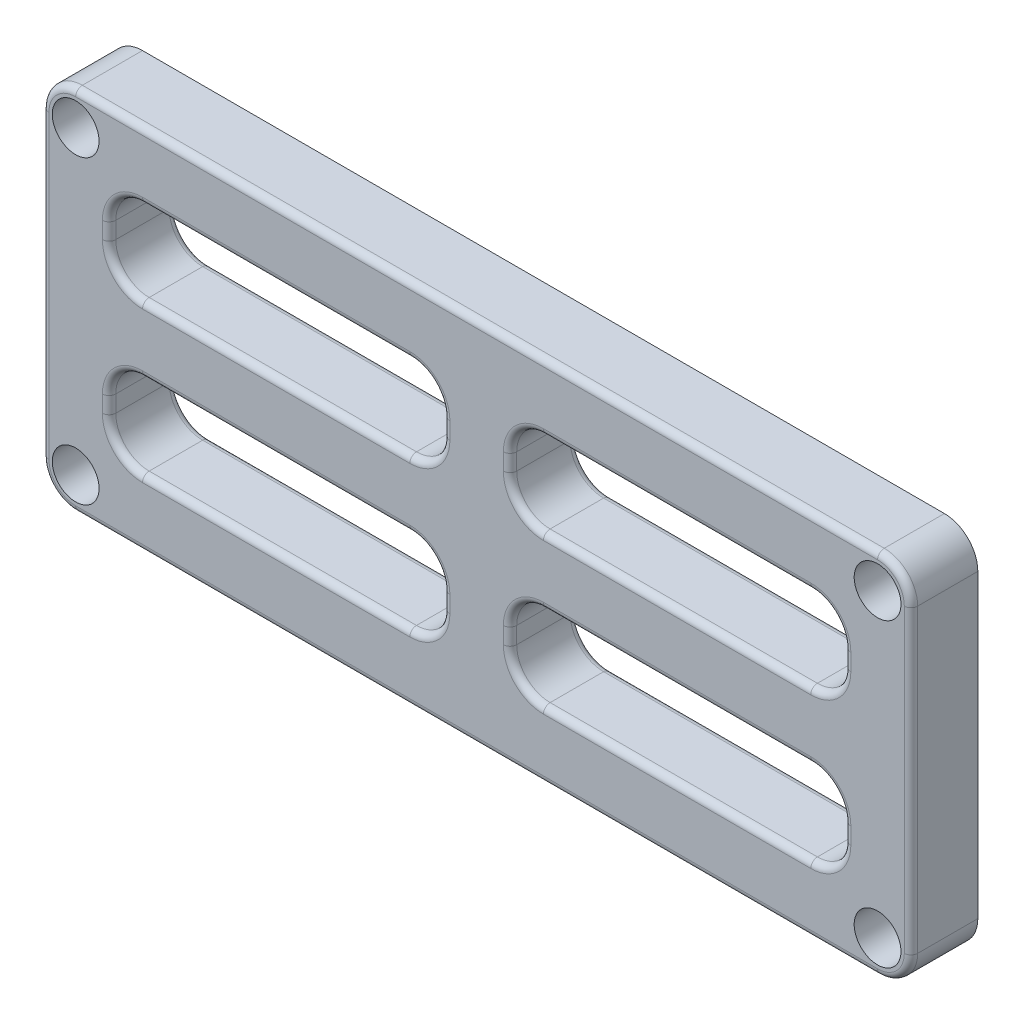
SolidWorks part; units mm, degrees
ref_plane "Front Plane" through (0, 0, 0) normal (0, 0, 1) x (1, 0, 0)
ref_plane "Top Plane" through (0, 0, 0) normal (0, 1, 0) x (1, 0, 0)
ref_plane "Right Plane" through (0, 0, 0) normal (1, 0, 0) x (0, 0, -1)
sketch "Sketch1" plane through (0, 0, 0) normal (0, 0, 1) x (1, 0, 0)
  line L0 (0, 0) -> (65, 0)
  line L1 (65, 0) -> (65, 27.5)
  line L2 (65, 27.5) -> (0, 27.5)
  line L3 (0, 27.5) -> (0, 0)
  line L4 (5, 22.5) -> (5, 5)
  line L5 (5, 5) -> (60, 5)
  line L6 (60, 5) -> (60, 22.5)
  line L7 (60, 22.5) -> (5, 22.5)
  dimension "D1" = 65
  dimension "D2" = 27.5
  dimension "D3" = 5
  dimension "D4" = 5
  dimension "D5" = 5
  dimension "D6" = 5
extrude "Boss-Extrude1" add sketch "Sketch1" along normal blind 5
sketch "Sketch2" plane through (0, 0, 5) normal (0, 0, 1) x (1, 0, 0)
  line L0 (5, 13.75) -> (5, 16.25)
  line L1 (5, 22.5) -> (5, 5) construction
  line L2 (5, 13.75) -> (5, 11.25)
  line L3 (32.5, 22.5) -> (35, 22.5)
  line L4 (60, 22.5) -> (5, 22.5) construction
  line L5 (32.5, 22.5) -> (30, 22.5)
  line L6 (60, 13.75) -> (60, 16.25)
  line L7 (60, 5) -> (60, 22.5) construction
  line L8 (60, 13.75) -> (60, 11.25)
  line L9 (32.5, 5) -> (35, 5)
  line L10 (5, 5) -> (60, 5) construction
  line L11 (32.5, 5) -> (30, 5)
  line L12 (5, 16.25) -> (30, 16.25)
  line L13 (30, 16.25) -> (30, 22.5)
  line L14 (35, 22.5) -> (35, 16.25)
  line L15 (35, 16.25) -> (60, 16.25)
  line L16 (60, 11.25) -> (35, 11.25)
  line L17 (35, 11.25) -> (35, 5)
  line L18 (30, 5) -> (30, 11.25)
  line L19 (30, 11.25) -> (5, 11.25)
  dimension "D1" = 2.5
  dimension "D2" = 2.5
  dimension "D3" = 2.5
  dimension "D4" = 2.5
  dimension "D5" = 2.5
  dimension "D6" = 2.5
  dimension "D7" = 2.5
  dimension "D8" = 2.5
extrude "Boss-Extrude2" add sketch "Sketch2" against normal blind 5
sketch "Sketch3" plane through (0, 0, 5) normal (0, 0, 1) x (1, 0, 0)
  line L0 (65, 27.5) -> (0, 27.5) construction
  line L1 (0, 27.5) -> (0, 0) construction
  line L2 (65, 0) -> (65, 27.5) construction
  line L3 (0, 0) -> (65, 0) construction
  circle A0 centre (2.5, 2.5) radius 1.75
  circle A1 centre (62.5, 2.5) radius 1.75
  circle A2 centre (62.5, 25) radius 1.75
  circle A3 centre (2.5, 25) radius 1.75
  dimension "D3" = 3.5
  dimension "D6" = 3.5
  dimension "D9" = 3.5
  dimension "D10" = 3.5
  dimension "D1" = 2.5
  dimension "D2" = 2.5
  dimension "D4" = 2.5
  dimension "D5" = 2.5
  dimension "D7" = 2.5
  dimension "D8" = 2.5
  dimension "D11" = 2.5
  dimension "D12" = 2.5
extrude "Cut-Extrude1" cut sketch "Sketch3" against normal through all
fillet "Fillet1" radius 2.5 20 edges at (5, 5, 2.5) (5, 11.25, 2.5) (5, 16.25, 2.5) (5, 22.5, 2.5) (30, 5, 2.5) (30, 16.25, 2.5) (30, 11.25, 2.5) (30, 22.5, 2.5) (60, 11.25, 2.5) (35, 11.25, 2.5) (35, 5, 2.5) (60, 5, 2.5) (60, 16.25, 2.5) (35, 16.25, 2.5) (35, 22.5, 2.5) (60, 22.5, 2.5) (65, 27.5, 2.5) (65, 0, 2.5) (0, 27.5, 2.5) (0, 0, 2.5)
fillet "Fillet2" radius 0.5 72 edges at (0, 13.75, 5) (32.5, 27.5, 5) (65, 13.75, 5) (32.5, 0, 5) (35.7322, 10.5178, 5) (35, 8.125, 0) (35, 8.125, 5) (35.7322, 5.7322, 5) (47.5, 5, 5) (59.2678, 5.7322, 5) (60, 8.125, 5) (59.2678, 10.5178, 5) (59.2678, 21.7678, 5) (60, 19.375, 5) (59.2678, 16.9822, 5) (47.5, 16.25, 5) (47.5, 16.25, 0) (35.7322, 16.9822, 5) (35, 19.375, 5) (35, 19.375, 0) (35.7322, 21.7678, 5) (29.2678, 21.7678, 5) (30, 19.375, 0) (30, 19.375, 5) (29.2678, 16.9822, 5) (17.5, 16.25, 0) (17.5, 16.25, 5) (5.7322, 16.9822, 5) (5, 19.375, 5) (5.7322, 21.7678, 5) (5.7322, 10.5178, 5) (5, 8.125, 5) (5.7322, 5.7322, 5) (17.5, 5, 5) (29.2678, 5.7322, 5) (30, 8.125, 0) (30, 8.125, 5) (29.2678, 10.5178, 5) (0.7322, 0.7322, 5) (0.7322, 26.7678, 5) (64.2678, 26.7678, 5) (64.2678, 0.7322, 5) (47.5, 11.25, 0) (47.5, 11.25, 5) (47.5, 22.5, 5) (17.5, 22.5, 5) (17.5, 11.25, 5) (17.5, 11.25, 0) (35.7322, 10.5178, 0) (35.7322, 5.7322, 0) (47.5, 5, 0) (59.2678, 5.7322, 0) (60, 8.125, 0) (59.2678, 10.5178, 0) (59.2678, 21.7678, 0) (60, 19.375, 0) (59.2678, 16.9822, 0) (35.7322, 16.9822, 0) (35.7322, 21.7678, 0) (5.7322, 10.5178, 0) (5, 8.125, 0) (5.7322, 5.7322, 0) (17.5, 5, 0) (29.2678, 5.7322, 0) (29.2678, 10.5178, 0) (29.2678, 21.7678, 0) (29.2678, 16.9822, 0) (5.7322, 16.9822, 0) (5, 19.375, 0) (5.7322, 21.7678, 0) (47.5, 22.5, 0) (17.5, 22.5, 0)
